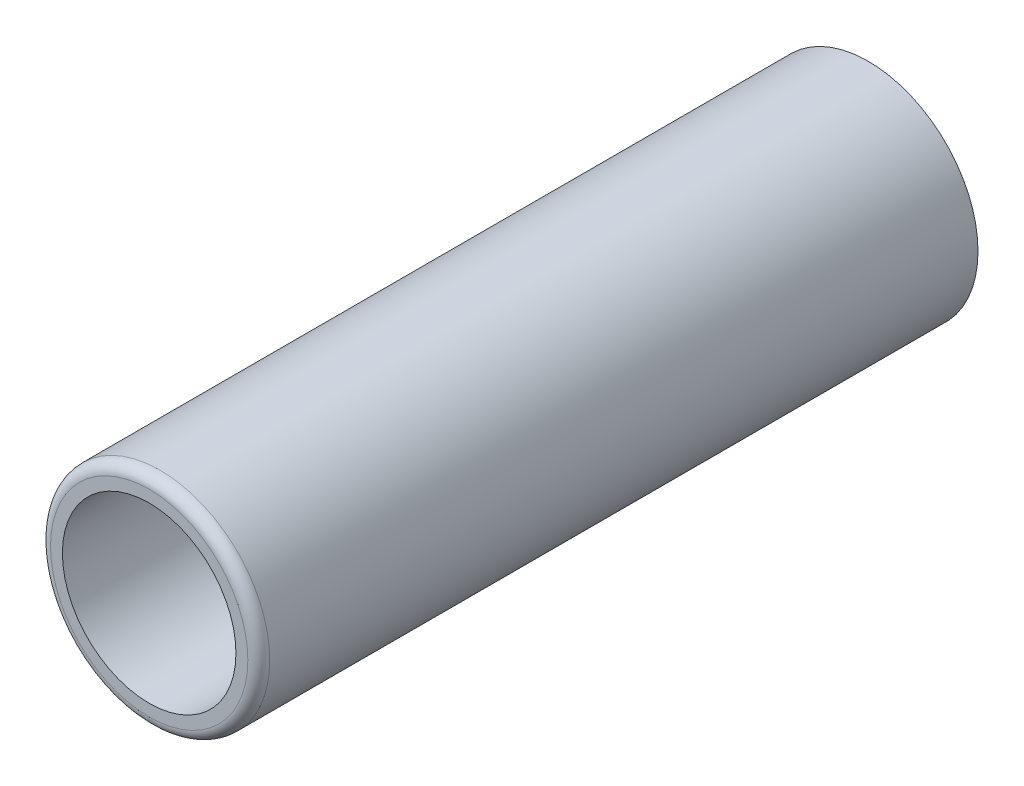
SolidWorks part; units mm, degrees
ref_plane "Front Plane" through (0, 0, 0) normal (0, 0, 1) x (1, 0, 0)
ref_plane "Top Plane" through (0, 0, 0) normal (0, 1, 0) x (1, 0, 0)
ref_plane "Right Plane" through (0, 0, 0) normal (1, 0, 0) x (0, 0, -1)
sketch "Sketch1" plane through (0, 0, 0) normal (0, 0, 1) x (1, 0, 0)
  line L0 (-9.525, 8.6993) -> (9.525, 8.6993)
  line L1 (9.525, 8.6993) -> (9.525, 0)
  line L2 (-9.525, 0) -> (-9.525, 8.6993)
  arc A0 (9.525, 0) -> (-9.525, 0) centre (0, 0) cw
  dimension "D1" = 19.05
  dimension "D2" = 8.6993
extrude "Extrude1" add sketch "Sketch1" along normal blind 58.42
sketch "Sketch2" plane through (0, 0, 58.42) normal (0, 0, 1) x (1, 0, 0)
  circle A0 centre (0, 0) radius 7.62
  dimension "D1" = 15.24
extrude "Extrude2" add sketch "Sketch2" along normal blind 50 separate body
sketch "Sketch3" plane through (0, 0, 108.42) normal (0, 0, 1) x (1, 0, 0)
  circle A0 centre (0, 0) radius 6.0325
  circle A1 centre (0, 0) radius 7.62 construction
  dimension "D1" = 1.5875
extrude "Extrude12" cut sketch "Sketch3" against normal through all
delete or keep bodies "Body-Delete1" type delete bodies bodies 116
fillet "Fillet1" radius 0.762 1 edges at (7.62, 0, 108.42)
